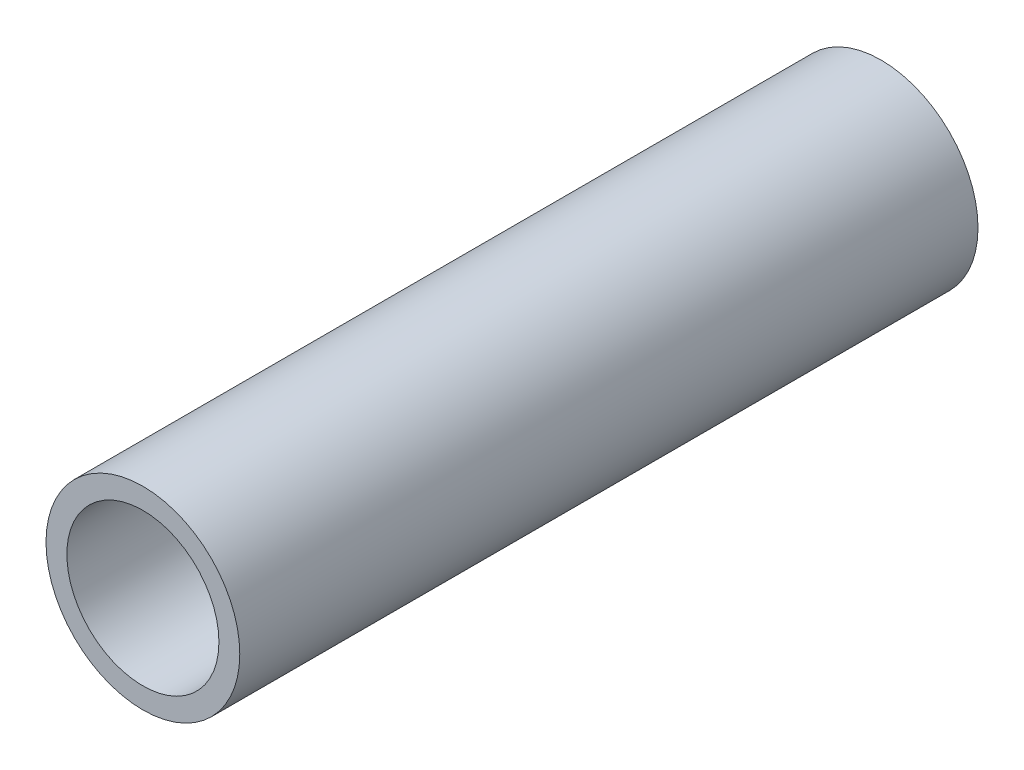
SolidWorks part; units mm, degrees
ref_plane "Front Plane" through (0, 0, 0) normal (0, 0, 1) x (1, 0, 0)
ref_plane "Top Plane" through (0, 0, 0) normal (0, 1, 0) x (1, 0, 0)
ref_plane "Right Plane" through (0, 0, 0) normal (1, 0, 0) x (0, 0, -1)
sketch "Sketch1" plane through (0, 0, 0) normal (0, 0, 1) x (1, 0, 0)
  circle A0 centre (0, 0) radius 10.4648
  circle A1 centre (0, 0) radius 13.335
  dimension "D1" = 2.8702
  dimension "D2" = 26.67
extrude "Boss-Extrude1" add sketch "Sketch1" along normal blind 101.6
